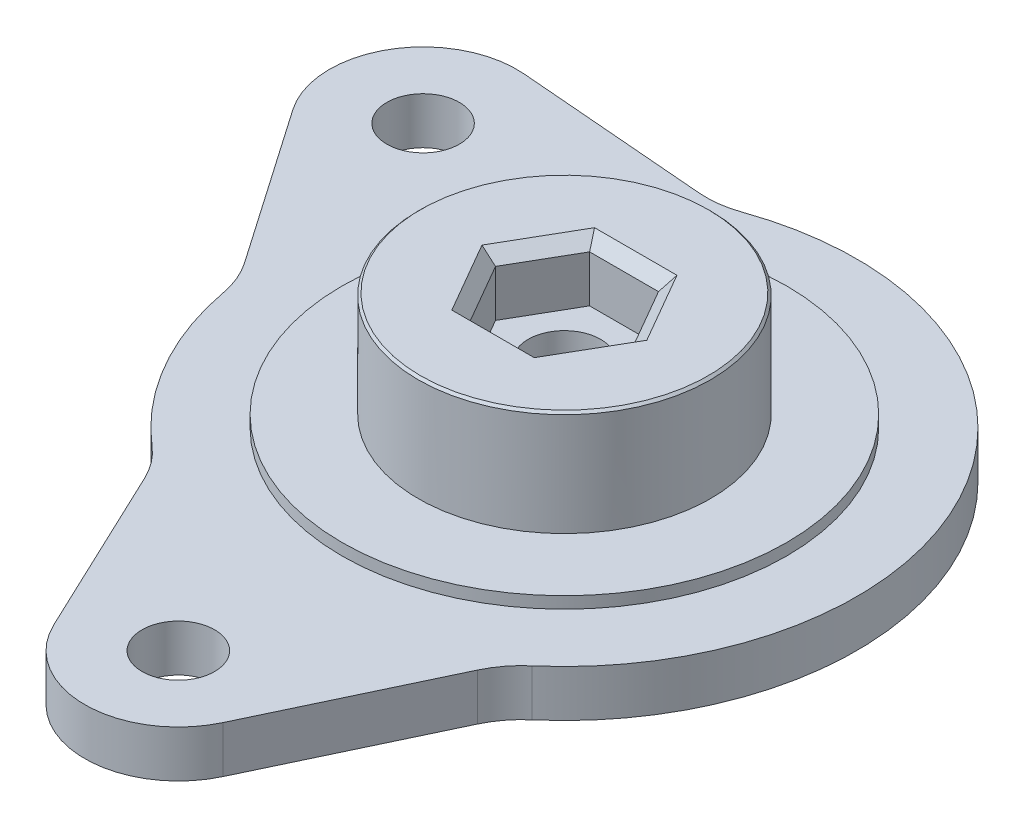
SolidWorks part; units mm, degrees
ref_plane "Front Plane" through (0, 0, 0) normal (0, 0, 1) x (1, 0, 0)
ref_plane "Top Plane" through (0, 0, 0) normal (0, 1, 0) x (1, 0, 0)
ref_plane "Right Plane" through (0, 0, 0) normal (1, 0, 0) x (0, 0, -1)
sketch "Sketch2" plane through (0, 0, 0) normal (0, 0, 1) x (1, 0, 0)
  line L0 (0, 0) -> (0, 12) construction
  line L1 (0, 0) -> (25, 0)
  line L2 (25, 0) -> (25, 4)
  line L3 (25, 4) -> (19, 4)
  line L4 (19, 4) -> (19, 5)
  line L5 (19, 5) -> (12.5, 5)
  line L6 (12.5, 5) -> (12.5, 14)
  line L7 (12.5, 14) -> (0, 14)
  line L8 (0, 14) -> (0, 0)
  dimension "D1" = 12
  dimension "D2" = 25
  dimension "D3" = 4
  dimension "D4" = 1
  dimension "D5" = 9
  dimension "D6" = 19
  dimension "D7" = 12.5
revolve "Revolve1" add sketch "Sketch2" angle 360 about L0
sketch "Sketch3" plane through (0, 14, 0) normal (0, 1, 0) x (1, 0, 0)
  line L1 (5.889, 0) -> (2.9445, 5.1)
  line L2 (2.9445, 5.1) -> (-2.9445, 5.1)
  line L3 (-2.9445, 5.1) -> (-5.889, 0)
  line L4 (-5.889, 0) -> (-2.9445, -5.1)
  line L5 (-2.9445, -5.1) -> (2.9445, -5.1)
  line L6 (2.9445, -5.1) -> (5.889, 0)
  circle A0 centre (0, 0) radius 5.1 construction
  dimension "D1" = 10.2
extrude "Cut-Extrude1" cut sketch "Sketch3" against normal blind 5
sketch "Sketch4" plane through (0, 0, 0) normal (0, 1, 0) x (1, 0, 0)
  circle A0 centre (0, 0) radius 3.1
  dimension "D1" = 6.2
extrude "Cut-Extrude2" cut sketch "Sketch4" along normal through all
chamfer "Chamfer1" distance 0.2 angle 45 1 edges at (0, 14, -12.5)
sketch "Sketch6" plane through (0, 0, 0) normal (0, 1, 0) x (1, 0, 0)
  line L0 (7.2316, -36.4211) -> (15, -20)
  line L1 (0, 0) -> (0, -33) construction
  line L2 (-7.2316, -36.4211) -> (-15, -20)
  circle A0 centre (0, 0) radius 25 construction
  circle A1 centre (0, 0) radius 25
  circle A2 centre (0, -33) radius 8
  circle A3 centre (0, -33) radius 3.1
  dimension "D1" = 16
  dimension "D3" = 15
  dimension "D2" = 6.2
extrude "Boss-Extrude1" add sketch "Sketch6" along normal up to surface (4 mm away)
pattern_circular "CirPattern1" count 2 every 120 about axis through (0, 0, 0) along (0, 1, 0) of "Boss-Extrude1"
fillet "Fillet2" radius 8 4 edges at (-9.8205, 2, -22.9904) (15, 2, 20) (-15, 2, 20) (-24.8205, 2, 2.9904)
chamfer "Chamfer2" distance 1 angle 45 6 edges at (-4.4167, 14, 2.55) (0, 14, 5.1) (4.4167, 14, 2.55) (4.4167, 14, -2.55) (-4.4167, 14, -2.55) (0, 14, -5.1)
fillet "Fillet3" [suppressed] radius 1
